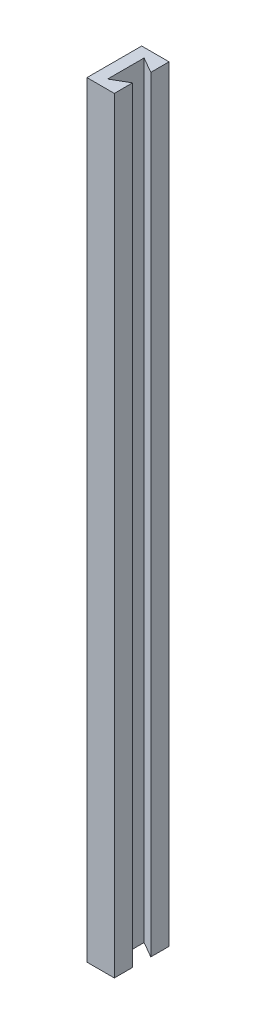
SolidWorks part; units mm, degrees
ref_plane "Front Plane" through (0, 0, 0) normal (0, 0, 1) x (1, 0, 0)
ref_plane "Top Plane" through (0, 0, 0) normal (0, 1, 0) x (1, 0, 0)
ref_plane "Right Plane" through (0, 0, 0) normal (1, 0, 0) x (0, 0, -1)
sketch "Sketch1" plane through (0, 0, 0) normal (0, 1, 0) x (1, 0, 0)
  line L0 (-28.0676, 0) -> (-28.0676, -25.4)
  line L1 (-28.0676, 0) -> (-15.3676, 0)
  line L2 (-15.3676, 0) -> (-15.3676, -8.4667)
  line L3 (-15.3676, -25.4) -> (-28.0676, -25.4)
  line L4 (-15.3676, -8.4667) -> (-22.6999, -4.2333)
  line L5 (-15.3676, -25.4) -> (-15.3676, -16.9333)
  line L6 (-15.3676, -16.9333) -> (-22.6999, -21.1667)
  line L7 (-22.6999, -21.1667) -> (-22.6999, -4.2333)
  dimension "D1" = 25.4
  dimension "D2" = 8.4667
  dimension "D3" = 8.4667
  dimension "D4" = 8.4667
  dimension "D5" = 8.4667
  dimension "D6" = 12.7
  dimension "D7" = 12.7
  dimension "D8" = 16.9333
extrude "Boss-Extrude2" add sketch "Sketch1" along normal blind 355.6 contours L2 L4 L7 L6 L5 L3 L0 L1
